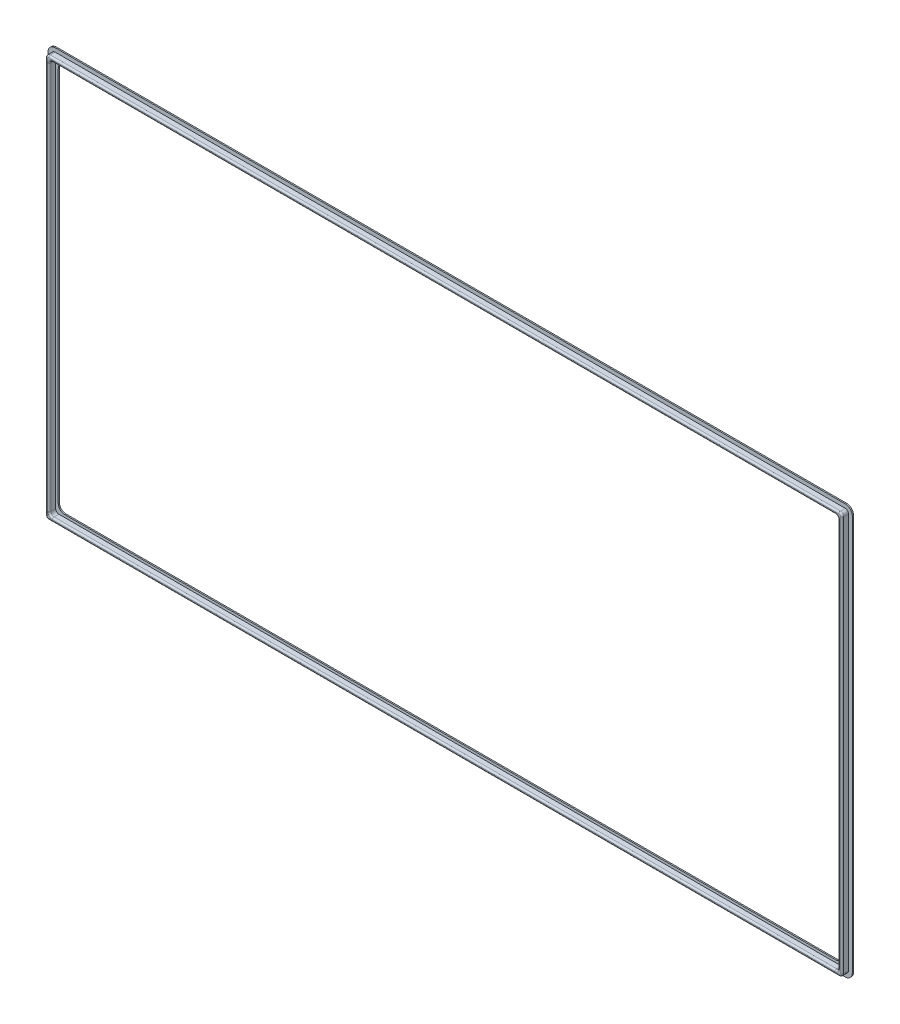
SolidWorks part; units mm, degrees
ref_plane "Ebene vorne" through (0, 0, 0) normal (0, 0, 1) x (1, 0, 0)
ref_plane "Ebene oben" through (0, 0, 0) normal (0, 1, 0) x (1, 0, 0)
ref_plane "Ebene rechts" through (0, 0, 0) normal (1, 0, 0) x (0, 0, -1)
sketch "Skizze1" plane through (0, 0, 0) normal (0, 0, 1) x (1, 0, 0)
  line L1 (0, 0) -> (250.4, 0)
  line L2 (0, 0) -> (0, -126.4)
  line L3 (0, -126.4) -> (250.4, -126.4)
  line L4 (250.4, 0) -> (250.4, -126.4)
  line L5 (0, 0) -> (250.4, -126.4) construction
  line L6 (0, -126.4) -> (250.4, 0) construction
  line L7 (1.2, -1.2) -> (249.2, -1.2)
  line L8 (1.2, -1.2) -> (1.2, -125.2)
  line L9 (1.2, -125.2) -> (249.2, -125.2)
  line L10 (249.2, -1.2) -> (249.2, -125.2)
  line L11 (1.2, -1.2) -> (249.2, -125.2) construction
  line L12 (1.2, -125.2) -> (249.2, -1.2) construction
  point P4 (125.2, -63.2)
  point P10 (125.2, -63.2)
  dimension "D1" = 1.2
  dimension "D2" = 1.2
  dimension "D3" = 126.4
  dimension "D4" = 250.4
extrude "Aufsatz-Linear austragen1" add sketch "Skizze1" along normal blind 2.4
fillet "Verrundung1" radius 1 8 edges at (249.2, -1.2, 1.2) (249.2, -125.2, 1.2) (250.4, -126.4, 1.2) (250.4, 0, 1.2) (1.2, -125.2, 1.2) (0, -126.4, 1.2) (1.2, -1.2, 1.2) (0, 0, 1.2)
fillet "Verrundung2" radius 0.5 16 edges at (1.4929, -1.4929, 2.4) (125.2, -1.2, 2.4) (248.9071, -1.4929, 2.4) (249.2, -63.2, 2.4) (248.9071, -124.9071, 2.4) (125.2, -125.2, 2.4) (1.4929, -124.9071, 2.4) (0.2929, -0.2929, 2.4) (125.2, 0, 2.4) (250.1071, -0.2929, 2.4) (250.4, -63.2, 2.4) (250.1071, -126.1071, 2.4) (125.2, -126.4, 2.4) (0.2929, -126.1071, 2.4) (1.2, -63.2, 2.4) (0, -63.2, 2.4)
sketch "Skizze2" plane through (0, 0, 0) normal (0, 0, -1) x (-1, 0, 0)
  line L0 (-1, 1.2) -> (-249.4, 1.2)
  line L1 (-251.6, -1) -> (-251.6, -125.4)
  line L2 (-249.4, -127.6) -> (-1, -127.6)
  line L3 (1.2, -125.4) -> (1.2, -1)
  line L4 (-250.4, -1) -> (-250.4, -125.4)
  line L5 (-249.4, -126.4) -> (-1, -126.4)
  line L6 (0, -125.4) -> (0, -1)
  line L7 (-1, 0) -> (-249.4, 0)
  line L8 (-250.4, -1) -> (-250.4, -125.4)
  line L9 (-249.4, -126.4) -> (-1, -126.4)
  line L10 (0, -125.4) -> (0, -1)
  line L11 (-1, 0) -> (-249.4, 0)
  arc A0 (-249.4, 1.2) -> (-251.6, -1) centre (-249.4, -1) ccw
  arc A1 (-251.6, -125.4) -> (-249.4, -127.6) centre (-249.4, -125.4) ccw
  arc A2 (-1, -127.6) -> (1.2, -125.4) centre (-1, -125.4) ccw
  arc A3 (1.2, -1) -> (-1, 1.2) centre (-1, -1) ccw
  arc A4 (-250.4, -125.4) -> (-249.4, -126.4) centre (-249.4, -125.4) ccw
  arc A5 (-1, -126.4) -> (0, -125.4) centre (-1, -125.4) ccw
  arc A6 (0, -1) -> (-1, 0) centre (-1, -1) ccw
  arc A7 (-249.4, 0) -> (-250.4, -1) centre (-249.4, -1) ccw
  arc A8 (-250.4, -125.4) -> (-249.4, -126.4) centre (-249.4, -125.4) ccw
  arc A9 (-1, -126.4) -> (0, -125.4) centre (-1, -125.4) ccw
  arc A10 (0, -1) -> (-1, 0) centre (-1, -1) ccw
  arc A11 (-249.4, 0) -> (-250.4, -1) centre (-249.4, -1) ccw
  dimension "D1" = 0
  dimension "D2" = 1.2
extrude "Aufsatz-Linear austragen2" add sketch "Skizze2" against normal blind 0.4
sketch "Skizze3" plane through (0, 0, 0) normal (0, 0, -1) x (-1, 0, 0)
  line L4 (-1, 1.2) -> (-249.4, 1.2)
  line L5 (-251.6, -1) -> (-251.6, -125.4)
  line L6 (-249.4, -127.6) -> (-1, -127.6)
  line L7 (1.2, -125.4) -> (1.2, -1)
  line L8 (-1, 1.2) -> (-249.4, 1.2)
  line L9 (-251.6, -1) -> (-251.6, -125.4)
  line L10 (-249.4, -127.6) -> (-1, -127.6)
  line L11 (1.2, -125.4) -> (1.2, -1)
  line L21 (-2, -2) -> (-248.4, -2)
  line L22 (-248.4, -2) -> (-248.4, -124.4)
  line L23 (-248.4, -124.4) -> (-2, -124.4)
  line L24 (-2, -124.4) -> (-2, -2)
  line L25 (-2, -2) -> (-248.4, -2)
  line L26 (-248.4, -2) -> (-248.4, -124.4)
  line L27 (-248.4, -124.4) -> (-2, -124.4)
  line L28 (-2, -124.4) -> (-2, -2)
  arc A4 (1.2, -1) -> (-1, 1.2) centre (-1, -1) ccw
  arc A5 (-249.4, 1.2) -> (-251.6, -1) centre (-249.4, -1) ccw
  arc A6 (-251.6, -125.4) -> (-249.4, -127.6) centre (-249.4, -125.4) ccw
  arc A7 (-1, -127.6) -> (1.2, -125.4) centre (-1, -125.4) ccw
  arc A8 (1.2, -1) -> (-1, 1.2) centre (-1, -1) ccw
  arc A9 (-249.4, 1.2) -> (-251.6, -1) centre (-249.4, -1) ccw
  arc A10 (-251.6, -125.4) -> (-249.4, -127.6) centre (-249.4, -125.4) ccw
  arc A11 (-1, -127.6) -> (1.2, -125.4) centre (-1, -125.4) ccw
  dimension "D1" = 0
  dimension "D2" = 3.2
extrude "Aufsatz-Linear austragen3" add sketch "Skizze3" against normal blind 0.4
fillet "Verrundung3" radius 2 4 edges at (2, -2, 0.2) (2, -124.4, 0.2) (248.4, -124.4, 0.2) (248.4, -2, 0.2)
